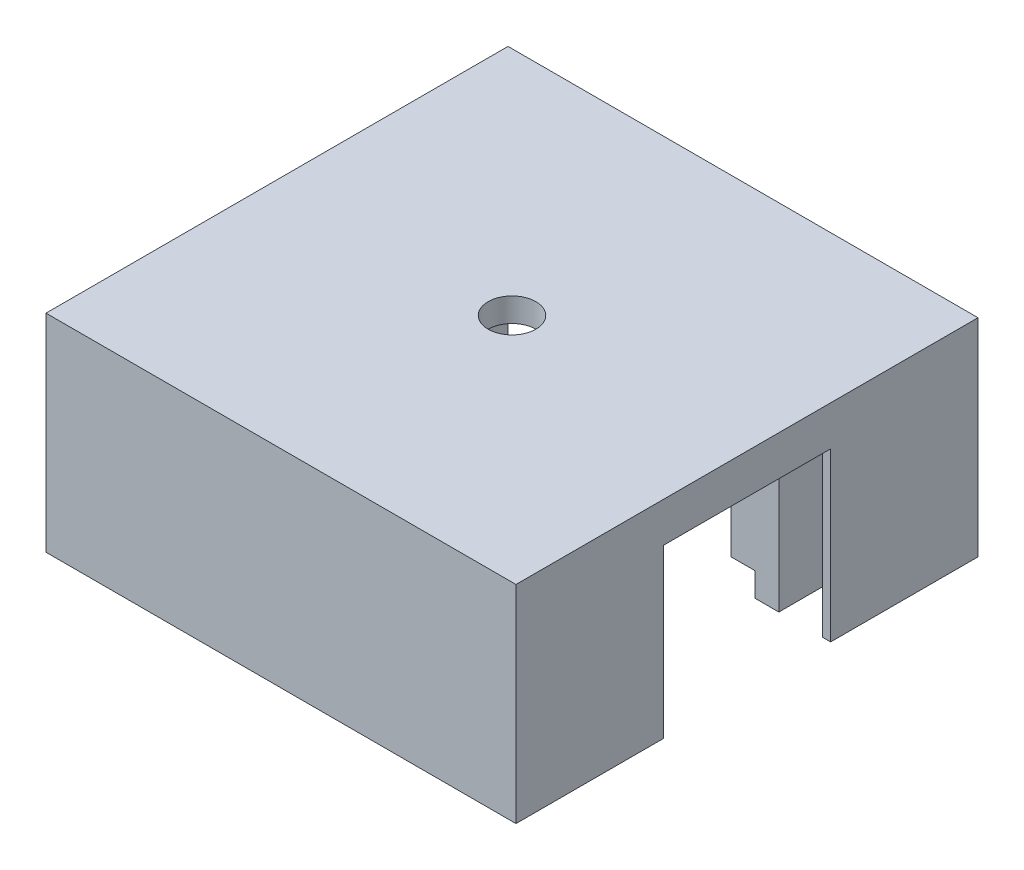
SolidWorks part; units mm, degrees
ref_plane "Front Plane" through (0, 0, 0) normal (0, 0, 1) x (1, 0, 0)
ref_plane "Top Plane" through (0, 0, 0) normal (0, 1, 0) x (1, 0, 0)
ref_plane "Right Plane" through (0, 0, 0) normal (1, 0, 0) x (0, 0, -1)
sketch "Sketch1" plane through (0, 0, 0) normal (0, 1, 0) x (1, 0, 0)
  line L0 (-23, -16.5) -> (23, 16.5) construction
  line L1 (-23, 16.5) -> (23, 16.5)
  line L2 (-23, 16.5) -> (-23, -16.5)
  line L3 (-23, -16.5) -> (23, -16.5)
  line L4 (23, 16.5) -> (23, -16.5)
  line L5 (23, -16.5) -> (-23, 16.5) construction
  point P2 (0, 0)
  dimension "D1" = 46
  dimension "D2" = 33
extrude "Boss-Extrude1" add sketch "Sketch1" along normal blind 23
sketch "Sketch3" plane through (0, 0, 0) normal (0, -1, 0) x (1, 0, 0)
  line L1 (-17, -10.5) -> (-17, -16.5)
  line L3 (23, -16.5) -> (-23, -16.5) construction
  line L7 (-17, -16.5) -> (5, -16.5)
  line L19 (-17, 16.5) -> (-17, 10.5)
  line L20 (-23, 16.5) -> (23, 16.5) construction
  line L21 (-17, 10.5) -> (-23, 10.5)
  line L22 (-23, -16.5) -> (-23, 16.5) construction
  line L23 (-23, 10.5) -> (-23, -10.5)
  line L24 (-23, -10.5) -> (-17, -10.5)
  line L26 (5, 16.5) -> (-17, 16.5)
  line L27 (5, 16.5) -> (5, 10.5)
  line L28 (5, 10.5) -> (17, 10.5)
  line L29 (17, 10.5) -> (17, -10.5)
  line L30 (17, -10.5) -> (5, -10.5)
  line L31 (5, -10.5) -> (5, -16.5)
  line L32 (23, 16.5) -> (23, -16.5) construction
  point P23 (23, 0)
  point P24 (17, 0)
  dimension "D1" = 6
  dimension "D2" = 6
  dimension "D3" = 6
  dimension "D5" = 22
  dimension "D6" = 21
extrude "Cut-Extrude2" cut sketch "Sketch3" against normal blind 20
sketch "Sketch5" plane through (0, 0, 0) normal (0, -1, 0) x (1, 0, 0)
  line L0 (-17, 13.5) -> (-20, 13.5)
  line L1 (-17, 16.5) -> (-17, 10.5) construction
  line L2 (-20, 13.5) -> (-20, 10.5)
  line L3 (-17, 10.5) -> (-23, 10.5) construction
  line L4 (-20, 10.5) -> (-23, 10.5)
  line L5 (-23, 10.5) -> (-23, 16.5)
  line L6 (-23, 10.5) -> (-23, 16.5) construction
  line L7 (-23, 16.5) -> (-17, 16.5)
  line L8 (-17, 16.5) -> (-17, 13.5)
  dimension "D1" = 3
extrude "Boss-Extrude2" add sketch "Sketch5" along normal blind 3
mirror "Mirror1" about plane through (0, 0, 0) normal (0, 0, 1) of "Boss-Extrude2"
mirror "Mirror2" about plane through (0, 0, 0) normal (1, 0, 0) of "Mirror1", "Boss-Extrude2"
sketch "Sketch6" plane through (0, 0, 0) normal (0, -1, 0) x (1, 0, 0)
  line L0 (23, 10.5) -> (17, 10.5)
  line L1 (17, 10.5) -> (17, -10.5)
  line L2 (17, -10.5) -> (23, -10.5)
  line L3 (23, -10.5) -> (23, 10.5)
extrude "Cut-Extrude3" cut sketch "Sketch6" against normal up to surface (20 mm away) up to face at (-5, 20, 0)
sketch "Sketch7" plane through (0, 20, 0) normal (0, -1, 0) x (1, 0, 0)
  line L0 (-23, 16.5) -> (23, -16.5) construction
  line L1 (23, 16.5) -> (-23, -16.5) construction
  circle A0 centre (0, 0) radius 3
  dimension "D1" = 6
extrude "Cut-Extrude5" cut sketch "Sketch7" against normal through all
sketch "Sketch8" plane through (0, 0, -16.5) normal (0, 0, -1) x (-1, 0, 0)
  line L0 (23, 23) -> (-23, 23)
  line L1 (-23, 23) -> (-23, 20)
  line L2 (-23, 23) -> (-23, -3) construction
  line L3 (-23, 20) -> (23, 20)
  line L4 (23, 20) -> (23, 23)
extrude "Boss-Extrude3" add sketch "Sketch8" along normal blind 6.5
mirror "Mirror3" about plane through (0, 0, 0) normal (0, 0, 1) of "Boss-Extrude3"
sketch "Sketch10" plane through (0, 20, 0) normal (0, -1, 0) x (1, 0, 0)
  line L1 (-23, -10.5) -> (-17, -10.5)
  line L2 (-23, -10.5) -> (-23, 10.5)
  line L3 (-23, 10.5) -> (-17, 10.5)
  line L4 (-17, -10.5) -> (-17, 10.5)
extrude "Boss-Extrude4" add sketch "Sketch10" along normal blind 20
sketch "Sketch11" plane through (-23, 0, 0) normal (-1, 0, 0) x (0, 0, 1)
  line L0 (-16.5, 20) -> (16.5, 20) construction
  line L2 (-10.5, 18) -> (10.5, 18)
  line L3 (-10.5, 18) -> (-10.5, -2)
  line L4 (-10.5, -2) -> (10.5, -2)
  line L5 (10.5, 18) -> (10.5, -2)
  dimension "D1" = 20
  dimension "D2" = 2
extrude "Cut-Extrude7" cut sketch "Sketch11" against normal up to next
sketch "Sketch13" plane through (23, 0, 0) normal (1, 0, 0) x (0, 0, -1)
  line L1 (-23, 20) -> (23, 20)
  line L2 (-23, 20) -> (-23, 23)
  line L3 (-23, 23) -> (23, 23)
  line L4 (23, 20) -> (23, 23)
extrude "Boss-Extrude6" add sketch "Sketch13" along normal blind 6.5
mirror "Mirror4" about plane through (0, 0, 0) normal (1, 0, 0) of "Boss-Extrude6"
sketch "Sketch12" plane through (0, 20, 0) normal (0, -1, 0) x (1, 0, 0)
  line L7 (-29.5, -23) -> (29.5, -23) construction
  line L9 (-6.5, -20.5) -> (-6.5, -23)
  line L10 (-6.5, -23) -> (6.5, -23)
  line L11 (6.5, -20.5) -> (6.5, -23)
  line L13 (6.5, -20.5) -> (26, -20.5)
  line L20 (-26.5, 20.5) -> (26.5, 20.5)
  line L21 (-26.5, 20.5) -> (-26.5, 19)
  line L22 (-26.5, 19) -> (26.5, 19)
  line L23 (26.5, 20.5) -> (26.5, 19)
  line L24 (5, 16.5) -> (17, 16.5) construction
  line L25 (-17, -16.5) -> (-23, -16.5) construction
  line L26 (-26, -20.5) -> (-6.5, -20.5)
  line L27 (-26, -20.5) -> (-26, -19)
  line L28 (-26, -19) -> (26, -19)
  line L29 (26, -20.5) -> (26, -19)
  point P0 (0, -19)
  point P16 (0, -23)
  point P21 (0, 19)
  dimension "D1" = 52
  dimension "D3" = 13
  dimension "D4" = 53
  dimension "D5" = 1.5
  dimension "D6" = 2.5
  dimension "D2" = 2.5
  dimension "D7" = 1.5
extrude "Cut-Extrude8" cut sketch "Sketch12" against normal blind 1.5 contours L26 L9 L10 L11 L13 L29 L28 L27
sketch "Sketch14" plane through (0, 0, -23) normal (0, 0, -1) x (-1, 0, 0)
  line L1 (-29.5, 20) -> (29.5, 20)
  line L2 (-29.5, 20) -> (-29.5, 23)
  line L3 (-29.5, 23) -> (29.5, 23)
  line L4 (29.5, 20) -> (29.5, 23)
extrude "Boss-Extrude7" add sketch "Sketch14" along normal blind 6
mirror "Mirror5" about plane through (0, 0, 0) normal (0, 0, 1) of "Boss-Extrude7"
sketch "Sketch15" plane through (0, 20, 0) normal (0, -1, 0) x (1, 0, 0)
  line L1 (-6.5, -23) -> (6.5, -23)
  line L2 (-6.5, -23) -> (-6.5, -23.75)
  line L3 (-6.5, -23.75) -> (6.5, -23.75)
  line L4 (6.5, -23) -> (6.5, -23.75)
  dimension "D1" = 0.75
extrude "Cut-Extrude9" cut sketch "Sketch15" against normal blind 1.5
sketch "Sketch16" plane through (0, 20, 0) normal (0, -1, 0) x (1, 0, 0)
  line L0 (28.5, 28) -> (28.5, -28)
  line L1 (28.5, -28) -> (-28.5, -28)
  line L2 (-28.5, -28) -> (-28.5, 28)
  line L3 (-28.5, 28) -> (28.5, 28)
  line L4 (-28.5, -10.5) -> (-29.5, -10.5)
  line L5 (-29.5, 29) -> (29.5, 29)
  line L6 (-29.5, 29) -> (-29.5, -29)
  line L7 (-29.5, -29) -> (29.5, -29)
  line L8 (29.5, 29) -> (29.5, -29)
  line L9 (23, 10.5) -> (20, 10.5) construction
  line L10 (-28.5, 10.5) -> (-29.5, 10.5)
  line L11 (-23, 10.5) -> (-20, 10.5) construction
  line L12 (-26.5, 28) -> (-26.5, 29)
  line L13 (26.5, 28) -> (26.5, 29)
  line L16 (28.5, 10.5) -> (29.5, 10.5)
  line L18 (28.5, -10.5) -> (29.5, -10.5)
  line L19 (23, -10.5) -> (20, -10.5) construction
  line L20 (-23, -10.5) -> (-20, -10.5) construction
  line M17 (-29.5, 29) -> (-29.5, -29)
  line M18 (-29.5, -29) -> (29.5, -29)
  line M19 (29.5, -29) -> (29.5, 29)
  line M20 (29.5, 29) -> (-29.5, 29)
  dimension "D1" = 1
  dimension "D2" = 1
  dimension "D3" = 1
  dimension "D4" = 1
extrude "Boss-Extrude8" add sketch "Sketch16" along normal blind 23 contours L3 L12 L5 L10 L2 M17 | L0 L16 L8 L13 L3 M20 | L18 L0 L1 L2 L4 M17 M18 M19
sketch "Sketch17" plane through (0, 0, -29) normal (0, 0, -1) x (-1, 0, 0)
  line L0 (29.5, 20) -> (-29.5, 20) construction
  line L1 (29.5, -3) -> (29.5, 23) construction
  line L2 (-29.5, 23) -> (-29.5, -3) construction
  line L3 (29.5, 23) -> (-29.5, 23) construction
  line L4 (29.5, 20) -> (-29.5, 20)
  line L5 (0, 20) -> (0, -3) construction
  line L6 (29.5, -3) -> (-29.5, -3) construction
  line L11 (-28.5, 10.5) -> (-28.5, -3)
  line L12 (28.5, 10.5) -> (28.5, -3)
  line L14 (28.5, -3) -> (-28.5, -3)
  line L15 (-28.5, 10.5) -> (28.5, 10.5)
  line L16 (13, 10.5) -> (-13, 10.5)
  circle A0 centre (13, 10.5) radius 9.5
  circle A1 centre (-13, 10.5) radius 9.5
  dimension "D3" = 19
  dimension "D4" = 26
  dimension "D5" = 13
  dimension "D7" = 1
  dimension "D1" = 3
  dimension "D8" = 1
extrude "Cut-Extrude11" cut sketch "Sketch17" against normal up to next
sketch "Sketch18" plane through (0, 20, 0) normal (0, -1, 0) x (1, 0, 0)
  line L1 (-26.5, 29) -> (26.5, 29)
  line L2 (-26.5, 29) -> (-26.5, 28)
  line L3 (-26.5, 28) -> (26.5, 28)
  line L4 (26.5, 29) -> (26.5, 28)
sketch "Sketch20" plane through (0, 20, 0) normal (0, -1, 0) x (1, 0, 0)
  line L0 (-17, 16.5) -> (-23, 16.5) construction
  line L1 (-26.5, 18.5) -> (26.5, 18.5)
  line L2 (-26.5, 18.5) -> (-26.5, 22)
  line L3 (-26.5, 22) -> (26.5, 22)
  line L4 (26.5, 18.5) -> (26.5, 22)
  point P6 (0, 22)
  dimension "D1" = 3.5
  dimension "D2" = 2
  dimension "D3" = 53
extrude "Boss-Extrude10" add sketch "Sketch20" along normal blind 11
sketch "Sketch22" plane through (0, 9, 0) normal (0, -1, 0) x (1, 0, 0)
  line L0 (-26.5, 22) -> (-26.5, 18.5) construction
  line L1 (-26.5, 21) -> (26.5, 21)
  line L2 (-26.5, 21) -> (-26.5, 19.5)
  line L3 (-26.5, 19.5) -> (26.5, 19.5)
  line L4 (26.5, 21) -> (26.5, 19.5)
  line L5 (26.5, 18.5) -> (26.5, 22) construction
  line L6 (26.5, 22) -> (-26.5, 22) construction
  dimension "D1" = 1.5
  dimension "D2" = 1
extrude "Cut-Extrude12" cut sketch "Sketch22" against normal blind 4
sketch "Sketch23" plane through (0, 0, 0) normal (0, -1, 0) x (1, 0, 0)
  line L1 (5, 16.5) -> (17, 16.5)
  line L2 (5, 16.5) -> (5, -16.5)
  line L3 (5, -16.5) -> (17, -16.5)
  line L4 (17, 16.5) -> (17, -16.5)
extrude "Cut-Extrude13" cut sketch "Sketch23" against normal up to surface (20 mm away) up to face at (0, 20, 3.2222)
sketch "Sketch25" plane through (0, 20, 0) normal (0, -1, 0) x (1, 0, 0)
  line L1 (-29.5, 10.5) -> (-23, 10.5)
  line L2 (-29.5, 10.5) -> (-29.5, -10.5)
  line L3 (-29.5, -10.5) -> (-23, -10.5)
  line L4 (-23, 10.5) -> (-23, -10.5)
extrude "Boss-Extrude11" add sketch "Sketch25" along normal blind 2
sketch "Sketch27" plane through (0, 9, 0) normal (0, -1, 0) x (1, 0, 0)
  line L1 (-26.5, 22) -> (26.5, 22)
  line L2 (-26.5, 22) -> (-26.5, 21)
  line L3 (-26.5, 21) -> (26.5, 21)
  line L4 (26.5, 22) -> (26.5, 21)
extrude "Boss-Extrude12" add sketch "Sketch27" along normal blind 12
extrude "Boss-Extrude13" add sketch "Sketch18" along normal blind 23 contours L1 L4 L3 L2
sketch "Sketch33" plane through (0, 20, 0) normal (0, -1, 0) x (1, 0, 0)
  line L1 (17, 10.5) -> (29.5, 10.5)
  line L2 (17, 10.5) -> (17, -10.5)
  line L3 (17, -10.5) -> (29.5, -10.5)
  line L4 (29.5, 10.5) -> (29.5, -10.5)
extrude "Boss-Extrude14" add sketch "Sketch33" along normal blind 2
sketch "Sketch34" plane through (-29.5, 0, 0) normal (-1, 0, 0) x (0, 0, 1)
  line L1 (16.5, -3) -> (16.5, 7)
  line L2 (29, -3) -> (10.5, -3) construction
  line L3 (10.5, 18) -> (10.5, -3) construction
  line L5 (21, -3) -> (21, 7)
  line L6 (21, 7) -> (16.5, 7)
  line L7 (21, -3) -> (16.5, -3)
  dimension "D1" = 6
  dimension "D2" = 4.5
  dimension "D3" = 10
extrude "Cut-Extrude14" cut sketch "Sketch34" against normal up to next
